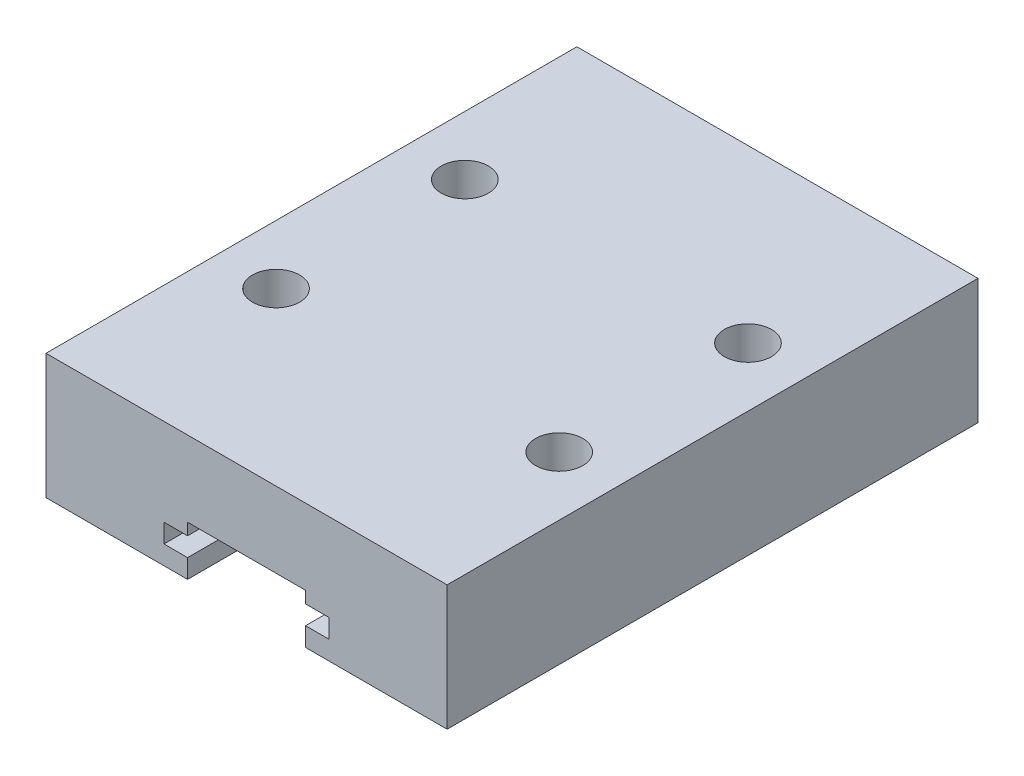
SolidWorks part; units mm, degrees
ref_plane "Front" through (0, 0, 0) normal (0, 0, 1) x (1, 0, 0)
ref_plane "Top" through (0, 0, 0) normal (0, 1, 0) x (1, 0, 0)
ref_plane "Right" through (0, 0, 0) normal (1, 0, 0) x (0, 0, -1)
sketch "草图1" plane through (0, 0, 0) normal (0, 0, 1) x (1, 0, 0)
  line L0 (-18.0658, -10.4809) -> (-12.0658, -10.4809)
  line L1 (-18.0658, -5.1809) -> (-1.0658, -5.1809)
  line L2 (-18.0658, -5.1809) -> (-18.0658, -10.4809)
  line L3 (-18.0658, -10.4809) -> (-1.0658, -10.4809)
  line L4 (-1.0658, -5.1809) -> (-1.0658, -10.4809)
  line L5 (-12.0658, -10.4809) -> (-12.0658, -8.3809)
  line L6 (-12.0658, -8.3809) -> (-12.0658, -8.8809)
  line L7 (-12.0658, -8.8809) -> (-13.0658, -8.8809)
  line L8 (-13.0658, -8.8809) -> (-13.0658, -9.6809)
  line L9 (-13.0658, -9.6809) -> (-12.0658, -9.6809)
  line L10 (-9.5658, -5.1809) -> (-9.5658, -10.4809)
  line L11 (-12.0658, -8.3809) -> (-7.0658, -8.3809)
  line L12 (-6.0658, -9.6809) -> (-7.0658, -9.6809)
  line L13 (-6.0658, -8.8809) -> (-6.0658, -9.6809)
  line L14 (-7.0658, -8.8809) -> (-6.0658, -8.8809)
  line L15 (-7.0658, -10.4809) -> (-7.0658, -8.3809)
  point P19 (-9.5658, -8.3809)
  dimension "D1" = 17
  dimension "D2" = 3.2
  dimension "D3" = 6
  dimension "D4" = 2.1
  dimension "D5" = 0.5
  dimension "D6" = 1
  dimension "D7" = 0.8
  dimension "D8" = 5.1809
  dimension "D9" = 1.0658
extrude "凸台-拉伸1" add sketch "草图1" along normal blind 22.5 contours L5 L11 L10 L1 L2 L0 L9 L8 L7 | L15 L3 L4 L1 L10 L11 L14 L13 L12
sketch "草图4" plane through (0, -5.1809, 0) normal (0, 1, 0) x (1, 0, 0)
  line L1 (-9.5658, -22.5) -> (-9.5658, 0) construction
  line L2 (-18.0658, -22.5) -> (-1.0658, -22.5) construction
  line L3 (-18.0658, 0) -> (-1.0658, 0) construction
  line L4 (-18.0658, -11.25) -> (-1.0658, -11.25) construction
  line L5 (-18.0658, -22.5) -> (-18.0658, 0) construction
  line L6 (-1.0658, -22.5) -> (-1.0658, 0) construction
  circle A0 centre (-15.5658, -7.25) radius 1
  circle A1 centre (-15.5658, -15.25) radius 1
  circle A2 centre (-3.5658, -7.25) radius 1
  circle A3 centre (-3.5658, -15.25) radius 1
  dimension "D1" = 2
  dimension "D2" = 2
  dimension "D3" = 2
  dimension "D4" = 2
  dimension "D5" = 8
  dimension "D6" = 12
extrude "切除-拉伸4" cut sketch "草图4" against normal blind 2
